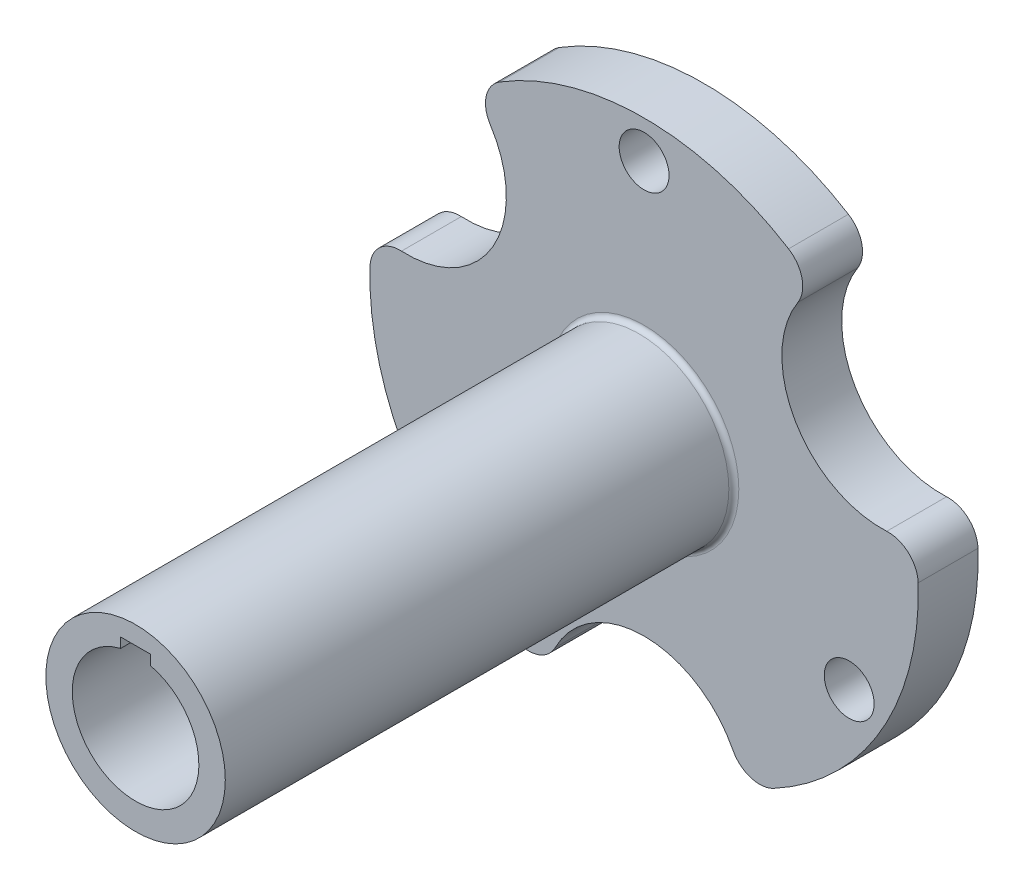
SolidWorks part; units mm, degrees
ref_plane "Front Plane" through (0, 0, 0) normal (0, 0, 1) x (1, 0, 0)
ref_plane "Top Plane" through (0, 0, 0) normal (0, 1, 0) x (1, 0, 0)
ref_plane "Right Plane" through (0, 0, 0) normal (1, 0, 0) x (0, 0, -1)
sketch "Sketch1" plane through (0, 0, 0) normal (0, 0, 1) x (1, 0, 0)
  line L0 (-20.5681, -11.875) -> (20.5681, -11.875) construction
  line L1 (0, 23.75) -> (-20.5681, -11.875) construction
  line L2 (0, 23.75) -> (20.5681, -11.875) construction
  line L3 (0, 0) -> (23.8157, 13.75) construction
  arc A0 (17.3244, 21.3568) -> (-17.3244, 21.3568) centre (0, 0) ccw
  circle A1 centre (0, 23.75) radius 2.5
  circle A2 centre (0, 0) radius 23.75 construction
  circle A3 centre (-20.5681, -11.875) radius 2.5
  circle A4 centre (20.5681, -11.875) radius 2.5
  arc A5 (17.3244, 21.3568) -> (27.1578, 4.325) centre (23.8157, 13.75) ccw
  arc A6 (9.8333, -25.6818) -> (-9.8333, -25.6818) centre (0, -27.5) ccw
  arc A7 (-27.1578, 4.325) -> (-17.3244, 21.3568) centre (-23.8157, 13.75) ccw
  arc A8 (-27.1578, 4.325) -> (-9.8333, -25.6818) centre (0, 0) ccw
  arc A9 (9.8333, -25.6818) -> (27.1578, 4.325) centre (0, 0) ccw
  circle A10 centre (0, 0) radius 6.35
  point P20 (0, 0)
  dimension "D1" = 55
  dimension "D2" = 47.5
  dimension "D3" = 5
  dimension "D4" = 10
  dimension "D6" = 12.7
  dimension "D5" = 3
extrude "Boss-Extrude1" add sketch "Sketch1" along normal blind 6
sketch "Sketch2" plane through (0, 0, 6) normal (0, 0, 1) x (1, 0, 0)
  circle A0 centre (0, 0) radius 9
  circle A1 centre (0, 0) radius 6.35
  dimension "D1" = 18
  dimension "D2" = 12.7
extrude "Boss-Extrude2" add sketch "Sketch2" along normal blind 51
fillet "Fillet1" radius 3 6 edges at (9.8333, -25.6818, 3) (-9.8333, -25.6818, 3) (27.1578, 4.325, 3) (17.3244, 21.3568, 3) (-27.1578, 4.325, 3) (-17.3244, 21.3568, 3)
sketch "Sketch3" plane through (0, 0, 57) normal (0, 0, 1) x (1, 0, 0)
  line L0 (-1.5, 6.1703) -> (-1.5, 7.1703)
  line L1 (-1.5, 7.1703) -> (1.5, 7.1703)
  line L2 (1.5, 7.1703) -> (1.5, 6.1703)
  circle A0 centre (0, 0) radius 6.35 construction
  arc A1 (1.5, 6.1703) -> (-1.5, 6.1703) centre (0, 0) ccw
  point P6 (0, 7.1703)
  dimension "D1" = 1
  dimension "D2" = 3
extrude "Cut-Extrude1" cut sketch "Sketch3" against normal blind 45 contours L1 L2 A1 L0
fillet "Fillet2" radius 0.5 1 edges at (9, 0, 6)
